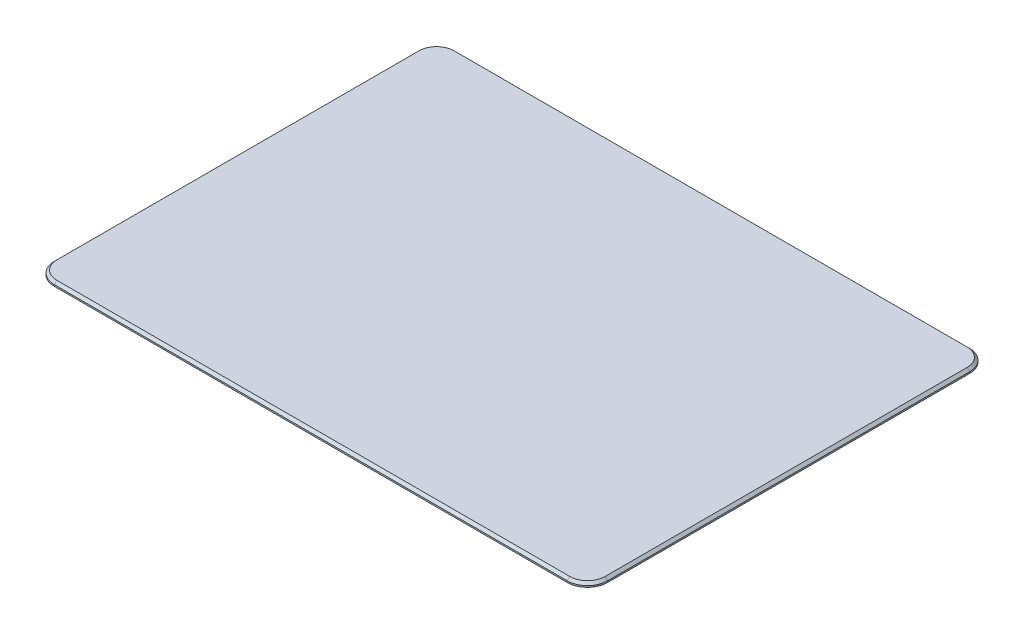
SolidWorks part; units mm, degrees
ref_plane "정면" through (0, 0, 0) normal (0, 0, 1) x (1, 0, 0)
ref_plane "윗면" through (0, 0, 0) normal (0, 1, 0) x (1, 0, 0)
ref_plane "우측면" through (0, 0, 0) normal (1, 0, 0) x (0, 0, -1)
sketch "스케치1" plane through (0, 0, 0) normal (0, 1, 0) x (1, 0, 0)
  line L1 (-275, -200) -> (275, -200)
  line L2 (-275, -200) -> (-275, 200)
  line L3 (-275, 200) -> (275, 200)
  line L4 (275, -200) -> (275, 200)
  line L5 (-275, -200) -> (275, 200) construction
  line L6 (-275, 200) -> (275, -200) construction
  point P0 (0, 0)
  dimension "D1" = 550
  dimension "D2" = 400
extrude "보스-돌출1" add sketch "스케치1" along normal blind 4
fillet "필렛1" radius 20 4 edges at (-275, 2, -200) (-275, 2, 200) (275, 2, -200) (275, 2, 200)
chamfer "모따기1" distance 2.5 angle 45 8 edges at (269.1421, 4, -194.1421) (275, 4, 0) (269.1421, 4, 194.1421) (0, 4, 200) (-269.1421, 4, 194.1421) (-275, 4, 0) (-269.1421, 4, -194.1421) (0, 4, -200)
